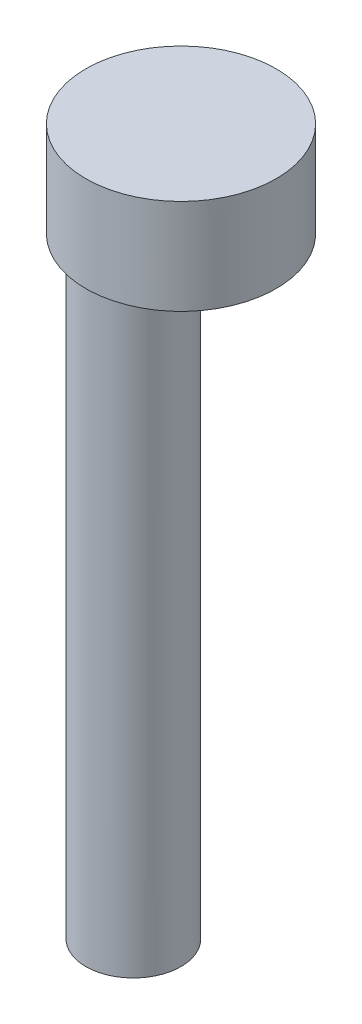
SolidWorks part; units mm, degrees
ref_plane "Front Plane" through (0, 0, 0) normal (0, 0, 1) x (1, 0, 0)
ref_plane "Top Plane" through (0, 0, 0) normal (0, 1, 0) x (1, 0, 0)
ref_plane "Right Plane" through (0, 0, 0) normal (1, 0, 0) x (0, 0, -1)
sketch "Sketch1" plane through (0, 0, 0) normal (0, 1, 0) x (1, 0, 0)
  circle A0 centre (0, 0) radius 0.75
  dimension "D1" = 1.5
extrude "Boss-Extrude1" add sketch "Sketch1" along normal blind 10
sketch "Sketch2" plane through (0, 10, 0) normal (0, 1, 0) x (1, 0, 0)
  circle A0 centre (0.75, 0) radius 1.5
  circle A1 centre (0, 0) radius 0.75 construction
  dimension "D1" = 3
  dimension "D2" = 0
extrude "Boss-Extrude2" add sketch "Sketch2" along normal blind 1.5 contours A0
ref_plane "Plane3" through (0, 9.5, 0) normal (0, -1, 0) x (-1, 0, 0)
